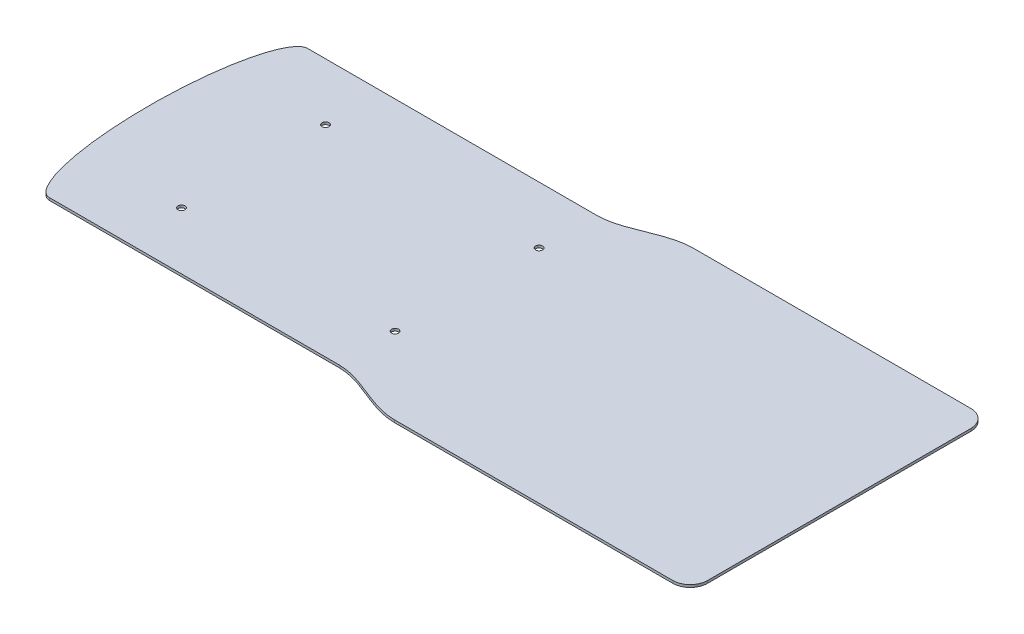
SolidWorks part; units mm, degrees
ref_plane "정면" through (0, 0, 0) normal (0, 0, 1) x (1, 0, 0)
ref_plane "윗면" through (0, 0, 0) normal (0, 1, 0) x (1, 0, 0)
ref_plane "우측면" through (0, 0, 0) normal (1, 0, 0) x (0, 0, -1)
sketch "스케치1" plane through (0, 0, 0) normal (0, 1, 0) x (1, 0, 0)
  line L1 (-139, 60) -> (139, 60)
  line L2 (-139, 60) -> (-139, -60)
  line L3 (-139, -60) -> (139, -60)
  line L4 (139, 60) -> (139, -60)
  line L5 (-139, 60) -> (139, -60) construction
  line L6 (-139, -60) -> (139, 60) construction
  point P0 (0, 0)
  dimension "D1" = 278
  dimension "D2" = 120
extrude "보스-돌출1" add sketch "스케치1" along normal blind 1
sketch "스케치2" plane through (0, 1, 0) normal (0, 1, 0) x (1, 0, 0)
  line L0 (-10, 60) -> (-10, -60) construction
  line L1 (139, 60) -> (-139, 60) construction
  line L2 (-139, -60) -> (139, -60) construction
  line L3 (-139, 60) -> (-139, -60) construction
  line L4 (20, 60) -> (20, -60) construction
  line L5 (-139, 0) -> (-10, 0) construction
  line L6 (-127, 60) -> (-127, -60) construction
  line L7 (-139, -52) -> (-10, -52) construction
  line L8 (-139, -52) -> (-139, 52) construction
  line L9 (-139, 52) -> (-10, 52) construction
  line L10 (-10, -52) -> (-10, 52) construction
  line L11 (-139, -52) -> (-10, 52) construction
  line L12 (-139, 52) -> (-10, -52) construction
  line L14 (-139, -52) -> (-10, -52)
  line L15 (-139, -52) -> (-139, -60)
  line L16 (-139, -60) -> (-10, -60)
  line L17 (-10, -52) -> (-10, -60)
  line L18 (-10, 60) -> (-139, 60)
  line L19 (-10, 60) -> (-10, 52)
  line L20 (-10, 52) -> (-139, 52)
  line L21 (-139, 60) -> (-139, 52)
  point P12 (-74.5, 0)
  dimension "D1" = 129
  dimension "D2" = 159
  dimension "D3" = 104
  dimension "D4" = 12
extrude "컷-돌출1" cut sketch "스케치2" against normal blind 1
sketch "스케치3" plane through (0, 1, 0) normal (0, 1, 0) x (1, 0, 0)
  line L0 (-127, 52) -> (-127, -52) construction
  line L1 (-139, 52) -> (-10, 52) construction
  line L2 (-10, -52) -> (-139, -52) construction
  line L3 (-139, 52) -> (-139, -52) construction
  line L4 (-127, 52) -> (-139, 52)
  line L5 (-139, 52) -> (-139, 0)
  line L6 (-139, 0) -> (-139, -52)
  line L7 (-139, -52) -> (-127, -52)
  ellipse E0 centre (-127, 0) end of major axis (-127, -52) minor radius 12
  line M2 (-10, 52) -> (-139, 52)
  line M3 (-139, 52) -> (-139, -52)
  line M4 (-139, -52) -> (-10, -52)
  dimension "D1" = 12
extrude "컷-돌출2" cut sketch "스케치3" against normal blind 1 contours E0 M2 M3 | E0 M3 M4
sketch "스케치4" plane through (0, 1, 0) normal (0, 1, 0) x (1, 0, 0)
  line L0 (20, 60) -> (20, -60) construction
  line L1 (139, 60) -> (-10, 60) construction
  line L2 (-10, -60) -> (139, -60) construction
  line L3 (-10, 52) -> (-10, -52) construction
  line L4 (-10, -52) -> (-127, -52) construction
  line L5 (139, 0) -> (-139, 0) construction
  line L6 (139, -60) -> (139, 60) construction
  line L7 (-10, 52) -> (-10, 60)
  line L8 (-10, 60) -> (20, 60)
  line L9 (-10, -52) -> (-10, -60)
  line L10 (-10, -60) -> (20, -60)
  ellipse E0 centre (-127, 0) end of major axis (-127, -52) minor radius 12 (-127, 52) -> (-127, -52) ccw construction
  spline S0 degree 3 poles (-10, 52) (0.6412, 52.3672) (9.3767, 59.9199) (20, 60) knots 0 0 0 0 1 1 1 1
  spline S1 degree 3 poles (-10, -52) (0.6412, -52.3672) (9.3767, -59.9199) (20, -60) knots 0 0 0 0 1 1 1 1
  dimension "D1" = 30
extrude "컷-돌출4" cut sketch "스케치4" against normal blind 1
sketch "스케치5" plane through (0, 1, 0) normal (0, 1, 0) x (1, 0, 0)
  line L0 (139, 0) -> (-139, 0) construction
  line L1 (139, -60) -> (139, 60) construction
  line L2 (139, 60) -> (20, 60) construction
  line L3 (132, 60) -> (139, 60)
  line L4 (139, 60) -> (139, 53)
  line L5 (139, -60) -> (139, -53)
  line L6 (132, -60) -> (139, -60)
  arc A0 (139, 53) -> (132, 60) centre (132, 53) ccw
  arc A1 (139, -53) -> (132, -60) centre (132, -53) cw
  ellipse E0 centre (-127, 0) end of major axis (-127, -52) minor radius 12 (-127, 52) -> (-127, -52) ccw construction
  dimension "D1" = 14
extrude "컷-돌출5" cut sketch "스케치5" against normal blind 1
sketch "스케치16" plane through (0, 1, 0) normal (0, 1, 0) x (1, 0, 0)
  line L0 (-127, 52) -> (-10, 52) construction
  line L1 (-106, -49) -> (-106, 49) construction
  line L2 (-106, 49) -> (4.3, 49) construction
  line L3 (-106, -49) -> (4.3, -49) construction
  line L4 (4.3, 49) -> (4.3, -49) construction
  circle A0 centre (-96.8513, 29.0311) radius 1.3998
  circle A1 centre (-96.8511, -28.968) radius 1.3998
  circle A2 centre (-10.8522, 29.0327) radius 1.3998
  circle A3 centre (-10.8511, -28.9678) radius 1.3998
  point P0 (-96.8511, -28.968)
  point P1 (-10.8511, -28.9678)
  point P2 (-10.8522, 29.0327)
  point P14 (4.3, 0)
  point P15 (-96.8513, 29.0311)
  dimension "D11" = 2.7996
  dimension "D12" = 2.7996
  dimension "D13" = 2.7996
  dimension "D14" = 2.7996
  dimension "D1" = 9.1487
  dimension "D2" = 98
  dimension "D3" = 110.3
  dimension "D4" = 19.9689
  dimension "D5" = 9.1489
  dimension "D6" = 20.032
  dimension "D7" = 20.0322
  dimension "D8" = 15.1511
  dimension "D9" = 15.1522
  dimension "D10" = 19.9673
  dimension "D15" = 22.9689
extrude "컷-돌출9" cut sketch "스케치16" against normal blind 10
sketch "스케치17" plane through (0, 1, 0) normal (0, 1, 0) x (1, 0, 0)
  line L0 (139, 0) -> (-139, 0) construction
  line L1 (139, -53) -> (139, 53) construction
  line L2 (-196.5554, 54) -> (178.1376, 54)
  line L3 (-196.5554, -54) -> (178.1376, -54)
  ellipse E0 centre (-127, 0) end of major axis (-127, -52) minor radius 12 (-127, 52) -> (-127, -52) ccw construction
  dimension "D1" = 54
